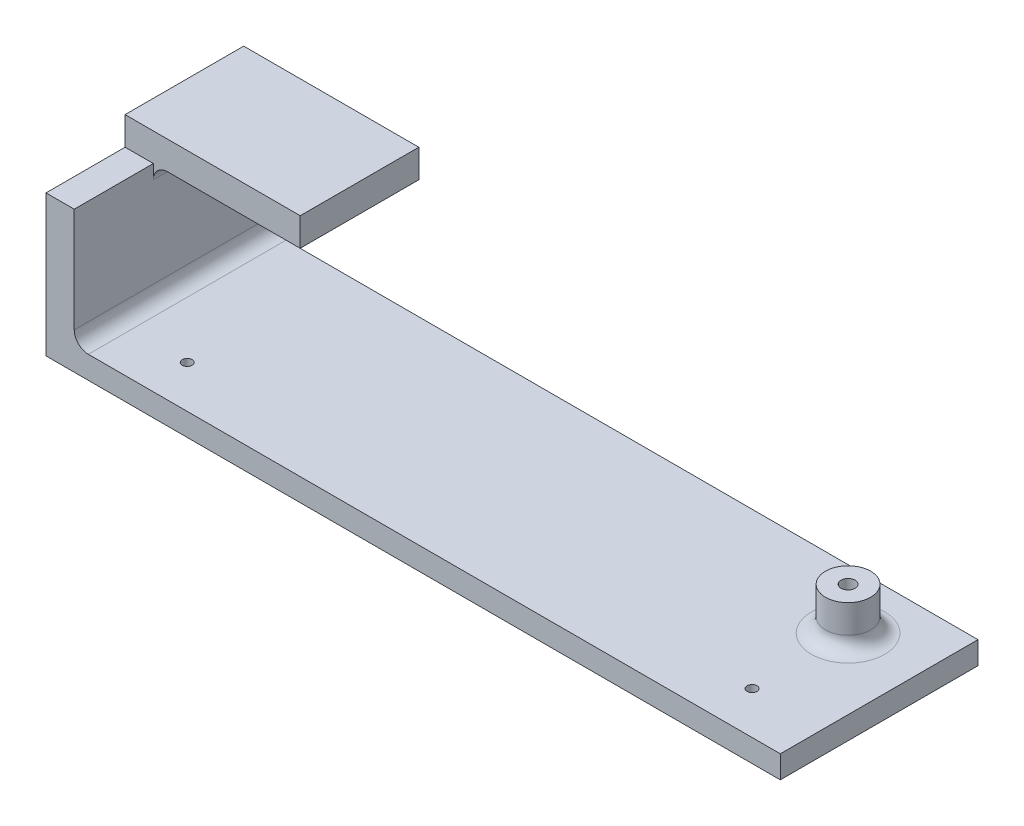
SolidWorks part; units mm, degrees
ref_plane "前视基准面" through (0, 0, 0) normal (0, 0, 1) x (1, 0, 0)
ref_plane "上视基准面" through (0, 0, 0) normal (0, 1, 0) x (1, 0, 0)
ref_plane "右视基准面" through (0, 0, 0) normal (1, 0, 0) x (0, 0, -1)
sketch "草图1" plane through (0, 0, 0) normal (0, 1, 0) x (1, 0, 0)
  line L1 (0, 0) -> (250, 0)
  line L2 (0, 0) -> (0, 70)
  line L3 (0, 70) -> (250, 70)
  line L4 (250, 0) -> (250, 70)
extrude "凸台-拉伸1" add sketch "草图1" along normal blind 8
sketch "草图2" plane through (0, 8, 0) normal (0, 1, 0) x (1, 0, 0)
  line L0 (0, 0) -> (25, 0) construction
  line L1 (0, 0) -> (250, 0) construction
  line L2 (25, 0) -> (25, 15) construction
  line L3 (25, 15) -> (225, 15) construction
  circle A0 centre (25, 15) radius 1.75
  circle A1 centre (225, 15) radius 1.75
extrude "切除-拉伸1" cut sketch "草图2" against normal blind 8
sketch "草图3" plane through (0, 0, 0) normal (0, -1, 0) x (1, 0, 0)
  line L0 (0, 0) -> (0, -70)
  line L1 (0, -70) -> (-10, -70)
  line L2 (-10, -70) -> (-10, 0)
  line L3 (-10, 0) -> (0, 0)
extrude "凸台-拉伸2" add sketch "草图3" against normal blind 50
sketch "草图4" plane through (-10, 0, 0) normal (-1, 0, 0) x (0, 0, 1)
  line L5 (-70, 50) -> (-28, 50)
  line L6 (-70, 50) -> (-70, 60)
  line L7 (-70, 60) -> (-28, 60)
  line L8 (-28, 50) -> (-28, 60)
extrude "凸台-拉伸3" add sketch "草图4" against normal blind 62
fillet "圆角2" radius 5 2 edges at (0, 8, -35) (0, 50, -49)
sketch "草图6" plane through (0, 8, 0) normal (0, 1, 0) x (1, 0, 0)
  line L1 (225, 70) -> (225, 49) construction
  line L2 (250, 70) -> (5, 70) construction
  circle A0 centre (225, 49) radius 8
  circle A1 centre (225, 49) radius 2.5
extrude "凸台-拉伸4" add sketch "草图6" along normal blind 15
fillet "圆角3" radius 5 1 edges at (225, 8, -57)
